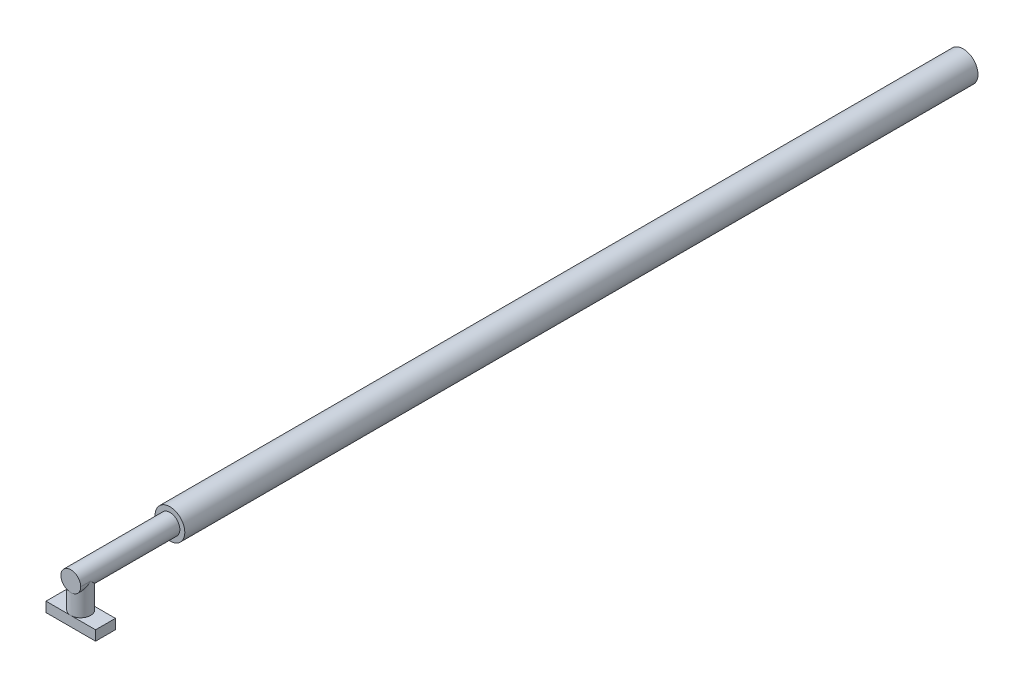
SolidWorks part; units mm, degrees
ref_plane "Спереди" through (0, 0, 0) normal (0, 0, 1) x (1, 0, 0)
ref_plane "Сверху" through (0, 0, 0) normal (0, 1, 0) x (1, 0, 0)
ref_plane "Справа" through (0, 0, 0) normal (1, 0, 0) x (0, 0, -1)
sketch "Эскиз1" plane through (0, 0, 0) normal (1, 0, 0) x (0, 0, -1)
  line L0 (0, 0) -> (49.1811, 0) construction
  line L1 (0, 0) -> (0, 10)
  line L3 (900, 15) -> (900, 0)
  line L4 (900, 0) -> (0, 0)
  line L5 (0, 10) -> (100, 10)
  line L6 (100, 10) -> (100, 15)
  line L7 (100, 15) -> (900, 15)
  dimension "D1" = 20
  dimension "D2" = 30
  dimension "D3" = 900
  dimension "D4" = 100
revolve "Повернуть1" add sketch "Эскиз1" angle 360 about L0
sketch "Эскиз2" plane through (0, 0, 0) normal (0, 1, 0) x (1, 0, 0)
  line L0 (0, 0) -> (0, 10) construction
  circle A0 centre (0, 10) radius 10
  dimension "D1" = 20
  dimension "D2" = 10
extrude "Бобышка-Вытянуть1" add sketch "Эскиз2" against normal blind 30
sketch "Эскиз3" plane through (0, -30, 0) normal (0, -1, 0) x (1, 0, 0)
  line L1 (-25, -20) -> (25, -20)
  line L2 (-25, -20) -> (-25, 0)
  line L3 (-25, 0) -> (25, 0)
  line L4 (25, -20) -> (25, 0)
  line L5 (-25, -20) -> (25, 0) construction
  line L6 (-25, 0) -> (25, -20) construction
  point P0 (0, -10)
  dimension "D1" = 50
  dimension "D2" = 20
extrude "Бобышка-Вытянуть2" add sketch "Эскиз3" along normal blind 10
